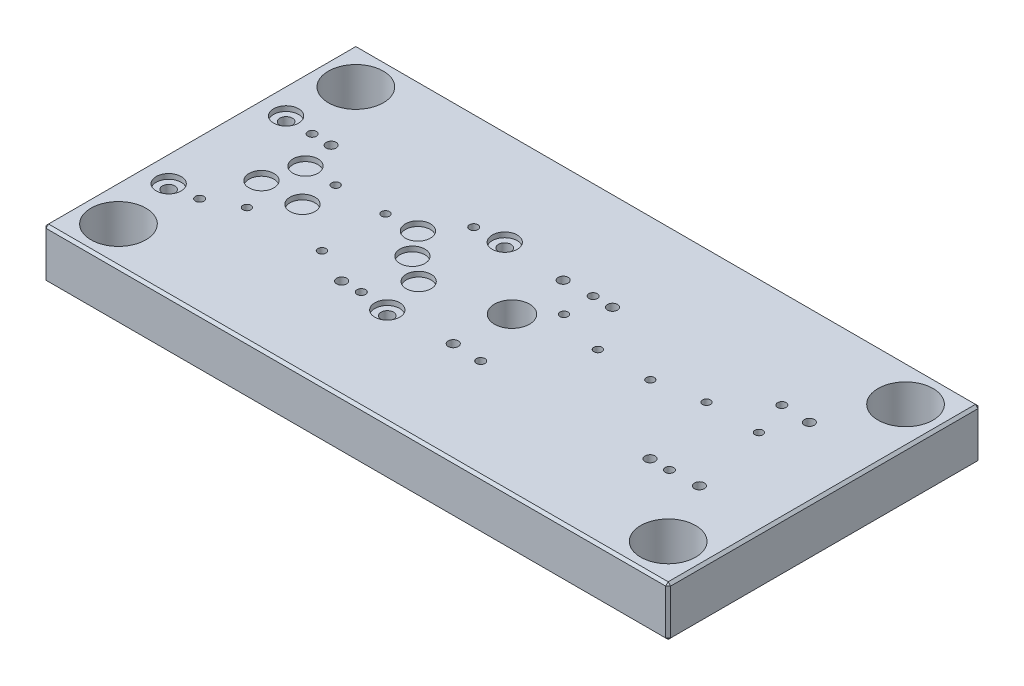
SolidWorks part; units mm, degrees
material "Plain Carbon Steel"
ref_plane "Front Plane" through (0, 0, 0) normal (0, 0, 1) x (1, 0, 0)
ref_plane "Top Plane" through (0, 0, 0) normal (0, 1, 0) x (1, 0, 0)
ref_plane "Right Plane" through (0, 0, 0) normal (1, 0, 0) x (0, 0, -1)
sketch "Sketch2" plane through (0, 0, 0) normal (0, 1, 0) x (1, 0, 0)
  line L1 (-250, -62.5) -> (250, -62.5)
  line L2 (-250, -62.5) -> (-250, 62.5)
  line L3 (-250, 62.5) -> (250, 62.5)
  line L4 (250, -62.5) -> (250, 62.5)
  line L5 (-250, -62.5) -> (250, 62.5) construction
  line L6 (-250, 62.5) -> (250, -62.5) construction
  point P0 (0, 0)
  dimension "D1" = 500
  dimension "D2" = 125
extrude "Boss-Extrude1" add sketch "Sketch2" along normal blind 40
sketch "Sketch5" plane through (0, 0, 0) normal (0, -1, 0) x (-1, 0, 0)
  line L4 (-250, 62.5) -> (-250, -62.5)
  line L5 (250, 62.5) -> (-250, 62.5)
  line L6 (250, -62.5) -> (250, 62.5)
  line L7 (-250, -62.5) -> (250, -62.5)
  line L8 (-250, 62.5) -> (-250, -62.5) construction
  line L9 (250, 62.5) -> (-250, 62.5) construction
  line L10 (250, -62.5) -> (250, 62.5) construction
  line L11 (-250, -62.5) -> (250, -62.5) construction
  dimension "D1" = 0
sketch "Sketch3" plane through (0, 0, -62.5) normal (0, 0, -1) x (-1, 0, 0)
  line L4 (-250, 0) -> (250, 0)
  line L5 (-250, 40) -> (-250, 0)
  line L6 (250, 40) -> (-250, 40)
  line L7 (250, 0) -> (250, 40)
  line L8 (-250, 0) -> (250, 0)
  line L9 (-250, 40) -> (-250, 0)
  line L10 (250, 40) -> (-250, 40)
  line L11 (250, 0) -> (250, 40)
  dimension "D1" = 0
extrude "Boss-Extrude2" add sketch "Sketch3" along normal blind 125
sketch "Sketch6" plane through (0, 0, 0) normal (0, -1, 0) x (-1, 0, 0)
  line L0 (-250, -62.5) -> (-250, 187.5) construction
  line L1 (250, -62.5) -> (-250, -62.5) construction
  line L2 (250, 187.5) -> (-250, 187.5) construction
  circle A0 centre (-220, 157.5) radius 22
  circle A1 centre (-220, -32.5) radius 22
  dimension "D1" = 44
  dimension "D2" = 30
  dimension "D3" = 30
  dimension "D4" = 30
extrude "Cut-Extrude1" cut sketch "Sketch6" against normal through all
mirror "Mirror1" about plane through (0, 0, 0) normal (1, 0, 0) of "Cut-Extrude1"
hole_wizard "M30x2.0 Tapped Hole1" positions "Sketch10" profile "Sketch9" tap size "M30x2.0" standard "ISO" end condition through all
sketch "Sketch10" plane through (0, 40, 0) normal (0, 1, 0) x (1, 0, 0)
  line L0 (-250, 187.5) -> (-250, -62.5) construction
  point P0 (0, 62.5)
  point P8 (-250, 62.5)
sketch "Sketch9" plane through (0, 40, -62.5) normal (1, 0, 0) x (0, 0, 1)
  line L0 (0, 0) -> (0, 40)
  line L1 (0, 40) -> (14, 40)
  line L2 (14, 40) -> (14, 0)
  line L5 (14, 0) -> (0, 0)
  line L11 (0, -6.35) -> (0, 107.95) construction
  dimension "Thru Tap Drill Dia." = 28
  dimension "Thru Tap Drill Depth" = 40
cosmetic thread "Hole Thread1" parameters "D2"=30
chamfer "Chamfer1" distance 2 angle 45 12 edges at (250, 0, -62.5) (250, 40, -62.5) (0, 40, -187.5) (250, 20, -187.5) (0, 0, -187.5) (-250, 0, -62.5) (-250, 40, -62.5) (-250, 20, -187.5) (250, 20, 62.5) (0, 0, 62.5) (0, 40, 62.5) (-250, 20, 62.5)
hole_wizard "M8 Tapped Hole1" positions "Sketch34" profile "Sketch12" tap size "M8" standard "ISO" end condition through all
sketch "Sketch34" plane through (0, 0, 0) normal (0, -1, 0) x (-1, 0, 0)
  point P0 (-171, 17.5)
  point P3 (-19.969, 17.5)
  point P6 (-19.969, 107.5)
  point P9 (-171, 107.5)
  point P12 (75.6325, 107.5)
  point P15 (205, 107.5)
  point P18 (205, 17.5)
  point P21 (75.6325, 17.5)
sketch "Sketch12" plane through (171, 0, -17.5) normal (1, 0, 0) x (0, 0, -1)
  line L0 (0, 0) -> (0, 40)
  line L1 (0, 40) -> (3.4, 40)
  line L2 (3.4, 40) -> (3.4, 0)
  line L5 (3.4, 0) -> (0, 0)
  line L11 (0, -6.35) -> (0, 107.95) construction
  dimension "Thru Tap Drill Dia." = 6.8
  dimension "Thru Tap Drill Depth" = 40
hole_wizard "Ø8.0mm Dowel Hole1" positions "Sketch16" profile "Sketch15" hole size "Ø8.0" standard "ISO" end condition through all
sketch "Sketch16" plane through (0, 0, 0) normal (0, -1, 0) x (-1, 0, 0)
  point P0 (-155.5, 17.5)
  point P3 (-35.469, 107.5)
  point P6 (91.1325, 17.259)
  point P9 (189.5, 107.2284)
sketch "Sketch15" plane through (155.5, 0, -17.5) normal (1, 0, 0) x (0, 0, -1)
  line L0 (0, 0) -> (0, 40)
  line L1 (0, 40) -> (4, 40)
  line L2 (4, 40) -> (4, 0)
  line L5 (4, 0) -> (0, 0)
  line L11 (0, -6.35) -> (0, 107.95) construction
  dimension "Thru Hole Dia." = 8
  dimension "Thru Hole Depth" = 40
hole_wizard "CBORE for M6 Hex Socket Head Cap Screw1" positions "Sketch19" profile "Sketch18" counterbore size "M6" standard "ISO" end condition through all
sketch "Sketch19" plane through (0, 0, 0) normal (0, -1, 0) x (-1, 0, 0)
  point P0 (-180.875, 79.28)
  point P6 (-100.875, 72.3524)
  point P9 (-58.875, 72.3524)
  point P12 (-20.875, 83.191)
  point P17 (-138.875, 79.28)
sketch "Sketch18" plane through (180.875, 0, -79.28) normal (1, 0, 0) x (0, 0, -1)
  line L0 (0, 0) -> (0, 40)
  line L1 (0, 40) -> (3.2, 40)
  line L3 (3.2, 40) -> (3.2, 6.4)
  line L4 (3.2, 6.4) -> (5.5, 6.4)
  line L5 (5.5, 6.4) -> (5.5, 0)
  line L7 (5.5, 0) -> (0, 0)
  line L11 (0, -6.35) -> (0, 107.95) construction
  dimension "Thru Hole Dia." = 6.4
  dimension "Thru Hole Depth" = 40
  dimension "C'Bore Dia." = 11
  dimension "C'Bore Depth" = 6.4
hole_wizard "CBORE for M6 Hex Socket Head Cap Screw2" positions "Sketch24" profile "Sketch23" counterbore size "M6" standard "ISO" end condition through all
sketch "Sketch24" plane through (0, 0, 0) normal (0, -1, 0) x (-1, 0, 0)
  point P0 (160, 81.36)
  point P3 (120.125, 81.36)
  point P6 (120, 30.34)
  point P9 (180, 30.34)
sketch "Sketch23" plane through (-160, 0, -81.36) normal (1, 0, 0) x (0, 0, -1)
  line L0 (0, 0) -> (0, 40)
  line L1 (0, 40) -> (3.2, 40)
  line L3 (3.2, 40) -> (3.2, 6.4)
  line L4 (3.2, 6.4) -> (5.5, 6.4)
  line L5 (5.5, 6.4) -> (5.5, 0)
  line L7 (5.5, 0) -> (0, 0)
  line L11 (0, -6.35) -> (0, 107.95) construction
  dimension "Thru Hole Dia." = 6.4
  dimension "Thru Hole Depth" = 40
  dimension "C'Bore Dia." = 11
  dimension "C'Bore Depth" = 6.4
sketch "Sketch25" plane through (0, 40, 0) normal (0, 1, 0) x (1, 0, 0)
  circle A0 centre (-227.8163, 15.5) radius 10 construction
  circle A1 centre (-52.8163, 15.5) radius 10 construction
  circle A2 centre (-52.8163, 109.5) radius 10 construction
  circle A3 centre (-227.8163, 109.5) radius 10 construction
  circle A4 centre (-185.3163, 82.5) radius 10 construction
  circle A5 centre (-192.8163, 54.78) radius 10 construction
  circle A6 centre (-160, 54.78) radius 10 construction
  circle A7 centre (-95.3163, 82.5) radius 10 construction
  circle A8 centre (-80, 62.78) radius 10 construction
  circle A9 centre (-60, 47.78) radius 10 construction
  circle A10 centre (-227.8163, 15.5) radius 10
  circle A11 centre (-52.8163, 15.5) radius 10
  circle A12 centre (-52.8163, 109.5) radius 10
  circle A13 centre (-227.8163, 109.5) radius 10
  circle A14 centre (-185.3163, 82.5) radius 10
  circle A15 centre (-192.8163, 54.78) radius 10
  circle A16 centre (-160, 54.78) radius 10
  circle A17 centre (-95.3163, 82.5) radius 10
  circle A18 centre (-80, 62.78) radius 10
  circle A19 centre (-60, 47.78) radius 10
extrude "Cut-Extrude2" cut sketch "Sketch25" against normal blind 4
hole_wizard "Ø10.0 (10) Diameter Hole1" positions "Sketch33" profile "Sketch28" hole size "Ø10.0" standard "ISO" end condition through all
sketch "Sketch33" plane through (0, 40, 0) normal (0, 1, 0) x (1, 0, 0)
  point P0 (-52.8163, 15.5)
  point P18 (-227.8163, 109.5)
  point P21 (-227.8163, 15.5)
  point P24 (-52.8163, 109.5)
sketch "Sketch28" plane through (-52.8163, 40, -15.5) normal (1, 0, 0) x (0, 0, 1)
  line L0 (0, 0) -> (0, 40)
  line L1 (0, 40) -> (5, 40)
  line L2 (5, 40) -> (5, 0)
  line L5 (5, 0) -> (0, 0)
  line L11 (0, -6.35) -> (0, 107.95) construction
  dimension "Thru Hole Dia." = 10
  dimension "Thru Hole Depth" = 40
sketch "Sketch35" plane through (0, 0, 0) normal (0, -1, 0) x (1, 0, 0)
  circle A0 centre (-52.8163, -109.5) radius 8.5
  circle A1 centre (-227.8163, -15.5) radius 8.5
  circle A2 centre (-227.8163, -109.5) radius 8.5
  circle A3 centre (-52.8163, -15.5) radius 8.5
  dimension "D1" = 17
extrude "Cut-Extrude3" cut sketch "Sketch35" against normal blind 24
hole_wizard "Ø8.0 (8) Diameter Hole2" positions "Sketch42" profile "Sketch41" hole size "Ø8.0" standard "ISO" end condition through all
sketch "Sketch42" plane through (0, 40, 0) normal (0, 1, 0) x (1, 0, 0)
  point P0 (-3.031, 106.5)
  point P3 (-3.031, 18.5)
  point P6 (194, 106.5)
  point P9 (194, 18.5)
sketch "Sketch41" plane through (-3.031, 40, -106.5) normal (1, 0, 0) x (0, 0, 1)
  line L0 (0, 0) -> (0, 40)
  line L1 (0, 40) -> (4, 40)
  line L2 (4, 40) -> (4, 0)
  line L5 (4, 0) -> (0, 0)
  line L11 (0, -6.35) -> (0, 107.95) construction
  dimension "Thru Hole Dia." = 8
  dimension "Thru Hole Depth" = 40
sketch "Sketch43" plane through (0, 0, 0) normal (0, -1, 0) x (1, 0, 0)
  circle A0 centre (194, -106.5) radius 7
  circle A1 centre (194, -18.5) radius 7
  circle A2 centre (-3.031, -18.5) radius 7
  circle A3 centre (-3.031, -106.5) radius 7
  dimension "D1" = 14
extrude "Cut-Extrude4" cut sketch "Sketch43" against normal blind 32
